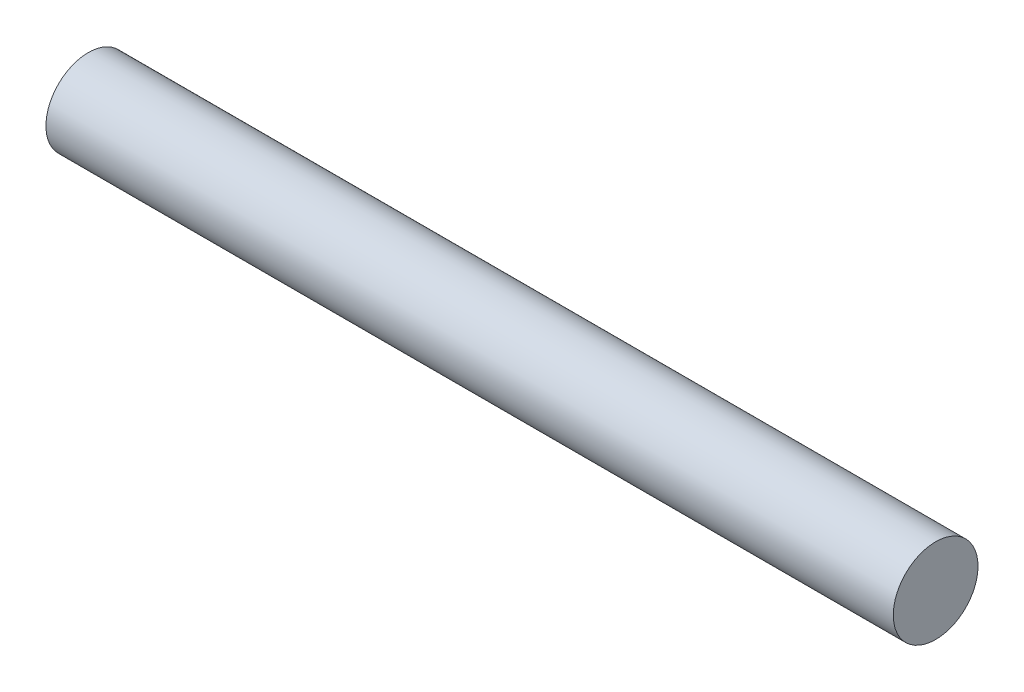
SolidWorks part; units mm, degrees
ref_plane "Front Plane" through (0, 0, 0) normal (0, 0, 1) x (1, 0, 0)
ref_plane "Top Plane" through (0, 0, 0) normal (0, 1, 0) x (1, 0, 0)
ref_plane "Right Plane" through (0, 0, 0) normal (1, 0, 0) x (0, 0, -1)
sketch "Sketch1" plane through (0, 0, 0) normal (1, 0, 0) x (0, 0, -1)
  circle A0 centre (0, 0) radius 12.7
  dimension "D1" = 25.4
extrude "Boss-Extrude1" add sketch "Sketch1" along normal blind 254
sketch3d "3DSketch1"
